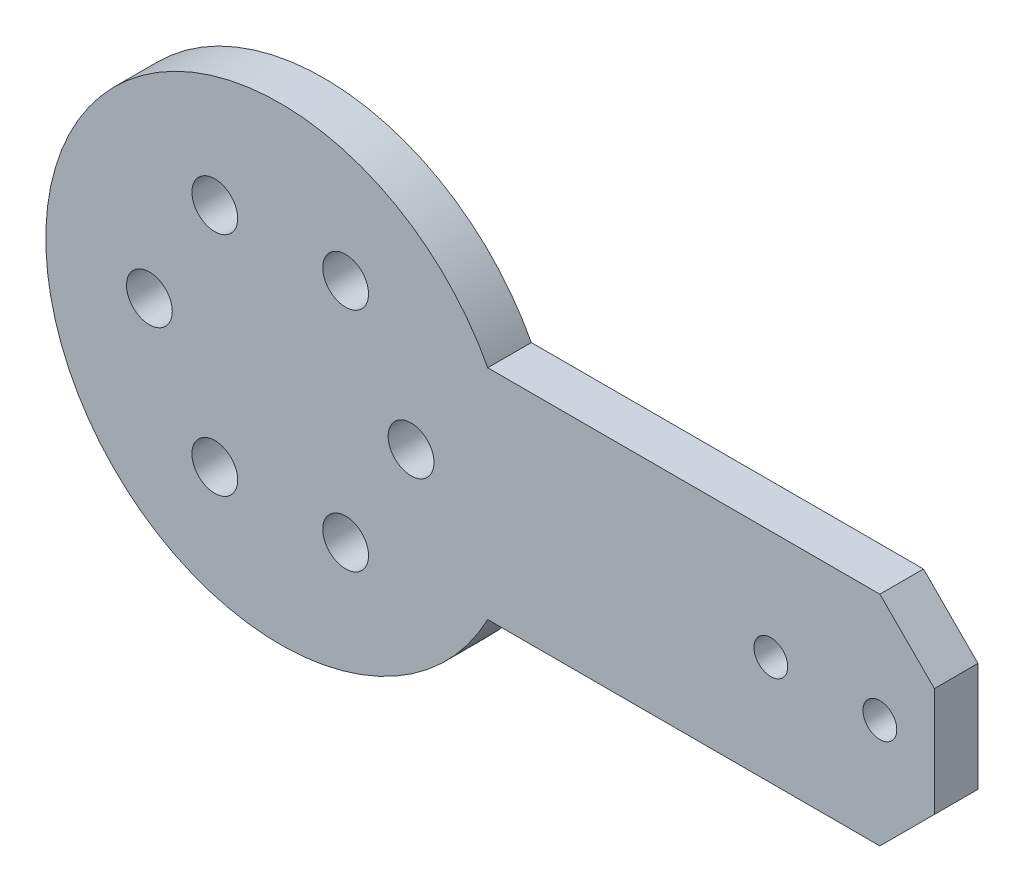
SolidWorks part; units mm, degrees
material "Thornel Mat VMA"
ref_plane "前视基准面" through (0, 0, 0) normal (0, 0, 1) x (1, 0, 0)
ref_plane "上视基准面" through (0, 0, 0) normal (0, 1, 0) x (1, 0, 0)
ref_plane "右视基准面" through (0, 0, 0) normal (1, 0, 0) x (0, 0, -1)
other "Configuration Table"
sketch "草图1" plane through (0, 0, 0) normal (0, 0, 1) x (1, 0, 0)
  line L0 (0, 0) -> (60, 0) construction
  line L1 (19.0329, 10) -> (60, 10)
  line L2 (60, -10) -> (60, 10)
  line L4 (60, -10) -> (19.0329, -10)
  circle A0 centre (0, 0) radius 21.5 construction
  circle A1 centre (12, 0) radius 2.1
  circle A2 centre (6, -10.3923) radius 2.1
  circle A3 centre (-6, -10.3923) radius 2.1
  circle A4 centre (-12, 0) radius 2.1
  circle A5 centre (-6, 10.3923) radius 2.1
  circle A6 centre (6, 10.3923) radius 2.1
  arc A7 (19.0329, 10) -> (19.0329, -10) centre (0, 0) ccw
  dimension "D2" = 43
  dimension "D4" = 4.2
  dimension "D7" = 10
  dimension "D1" = 60
  dimension "D3" = 12
  dimension "D6" = 10
  dimension "D5" = 6
extrude "凸台-拉伸1" add sketch "草图1" along normal blind 4
chamfer "倒角1" distance 5 angle 45 2 edges at (60, -10, 2) (60, 10, 2)
sketch "草图2" plane through (0, 0, 4) normal (0, 0, 1) x (1, 0, 0)
  line L0 (60, 0) -> (0, 0) construction
  line L1 (60, -5) -> (60, 5) construction
  circle A0 centre (55, 0) radius 1.55
  circle A1 centre (45, 0) radius 1.55
  dimension "D3" = 3.1
  dimension "D4" = 3.1
  dimension "D1" = 5
  dimension "D2" = 10
extrude "切除-拉伸1" cut sketch "草图2" against normal through all
